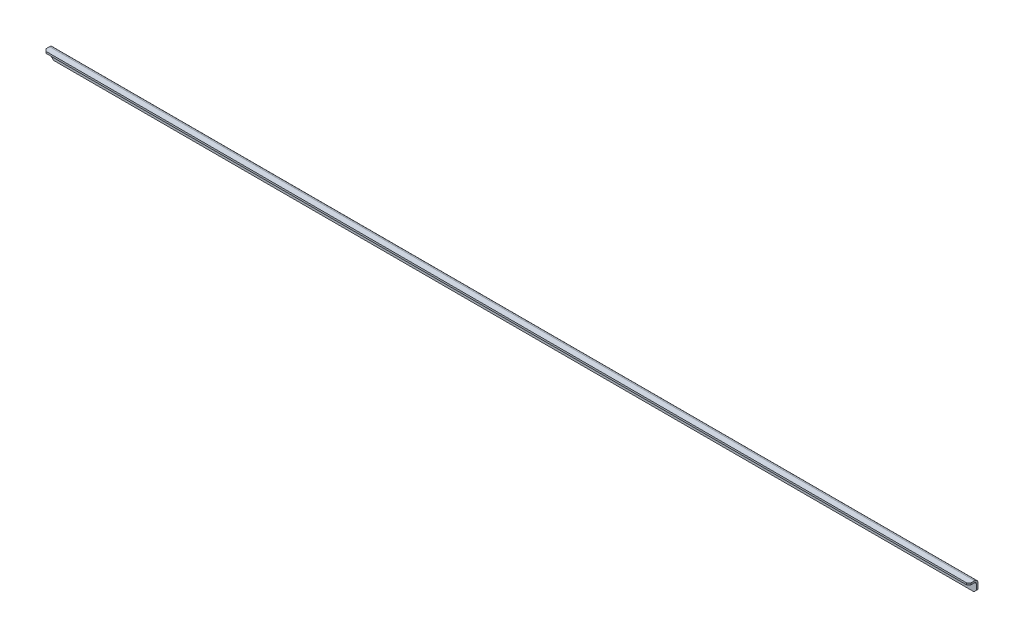
SolidWorks part; units mm, degrees
ref_plane "Front Plane" through (0, 0, 0) normal (0, 0, 1) x (1, 0, 0)
ref_plane "Top Plane" through (0, 0, 0) normal (0, 1, 0) x (1, 0, 0)
ref_plane "Right Plane" through (0, 0, 0) normal (1, 0, 0) x (0, 0, -1)
sketch "Sketch1" plane through (0, 0, 0) normal (1, 0, 0) x (0, 0, -1)
  line L0 (0, 0) -> (0, 10)
  line L1 (0, 10) -> (-8, 10)
  line L2 (-8, 10) -> (-8, 8.5)
  line L3 (-8, 8.5) -> (-1.5, 8.5)
  line L4 (-1.5, 8.5) -> (-1.5, 0)
  line L5 (-1.5, 0) -> (0, 0)
  dimension "FIX_1" = 8
  dimension "FIX_2" = 1.5
  dimension "FIX_3" = 10
extrude "Boss-Extrude1" add sketch "Sketch1" along normal blind 800
fillet "Fillet1" radius 3 1 edges at (400, 10, 0)
fillet "Fillet2" radius 1.5 1 edges at (400, 8.5, 1.5)
chamfer "Chamfer1" distance 2 4 edges at (800, 0, 0.75) (0, 0, 0.75) (800, 9.25, 8) (0, 9.25, 8)
